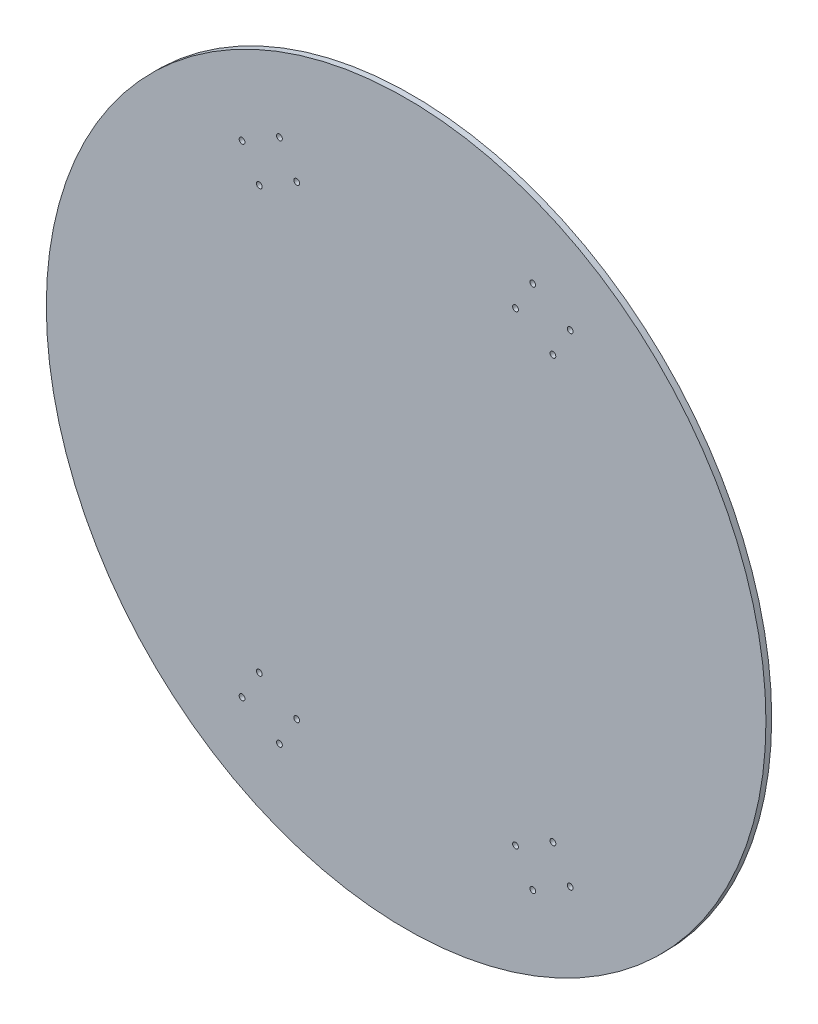
SolidWorks part; units mm, degrees
material "1345 Alloy"
ref_plane "Front Plane" through (0, 0, 0) normal (0, 0, 1) x (1, 0, 0)
ref_plane "Top Plane" through (0, 0, 0) normal (0, 1, 0) x (1, 0, 0)
ref_plane "Right Plane" through (0, 0, 0) normal (1, 0, 0) x (0, 0, -1)
sketch "Sketch1" plane through (0, 0, 0) normal (0, 0, 1) x (1, 0, 0)
  circle A0 centre (0, 0) radius 250
  dimension "D1" = 500
extrude "Boss-Extrude1" add sketch "Sketch1" along normal blind 4
sketch "Sketch2" plane through (0, 0, 4) normal (0, 0, 1) x (1, 0, 0)
  line L0 (0, 0) -> (163.2381, 0) construction
  line L1 (-233.2381, 90) -> (-163.2381, -90) construction
  line L11 (163.2381, -90) -> (163.2381, 90)
  line L12 (-163.2381, 0) -> (0, 0) construction
  line L13 (163.2381, 90) -> (233.2381, -90) construction
  line L14 (163.2381, 90) -> (233.2381, 90)
  line L15 (163.2381, -90) -> (233.2381, -90)
  line L16 (-233.2381, 90) -> (-163.2381, 90)
  line L18 (-233.2381, -90) -> (-163.2381, -90)
  line L19 (-163.2381, 90) -> (-163.2381, -90)
  line L20 (-163.2381, 90) -> (-233.2381, -90) construction
  line L21 (233.2381, 90) -> (163.2381, -90) construction
  circle A0 centre (0, 0) radius 250 construction
  arc A2 (-233.2381, 90) -> (-233.2381, -90) centre (0, 0) ccw
  arc A3 (233.2381, -90) -> (233.2381, 90) centre (0, 0) ccw
  point P18 (0, 0)
  dimension "D1" = 70
  dimension "D3" = 70
extrude "Cut-Extrude1" [suppressed] cut sketch "Sketch2" against normal blind 10
sketch "Sketch5" plane through (0, 0, 4) normal (0, 0, 1) x (1, 0, 0)
  line L8 (-113.9904, 167.4371) -> (-101.9904, 146.6525) construction
  line L10 (88.0096, 182.4371) -> (76.0096, 161.6525) construction
  line L11 (-101.9904, 146.6525) -> (-76.0096, 161.6525) construction
  line L14 (-76.0096, 161.6525) -> (-88.0096, 182.4371) construction
  line L18 (-88.0096, 182.4371) -> (-113.9904, 167.4371) construction
  line L19 (-88.0096, 182.4371) -> (-101.9904, 146.6525) construction
  line L20 (-113.9904, 167.4371) -> (-76.0096, 161.6525) construction
  line L21 (0, 0) -> (-95, 164.5448) construction
  line L22 (76.0096, 161.6525) -> (101.9904, 146.6525) construction
  line L23 (101.9904, 146.6525) -> (113.9904, 167.4371) construction
  line L24 (113.9904, 167.4371) -> (88.0096, 182.4371) construction
  line L29 (113.9904, 167.4371) -> (76.0096, 161.6525) construction
  line L34 (88.0096, 182.4371) -> (101.9904, 146.6525) construction
  line L39 (0, 0) -> (95, 164.5448) construction
  line L59 (113.9904, -167.4371) -> (101.9904, -146.6525) construction
  line L64 (101.9904, -146.6525) -> (76.0096, -161.6525) construction
  line L69 (76.0096, -161.6525) -> (88.0096, -182.4371) construction
  line L74 (88.0096, -182.4371) -> (113.9904, -167.4371) construction
  line L84 (88.0096, -182.4371) -> (101.9904, -146.6525) construction
  line L85 (113.9904, -167.4371) -> (76.0096, -161.6525) construction
  line L86 (0, 0) -> (95, -164.5448) construction
  line L87 (-88.0096, -182.4371) -> (-76.0096, -161.6525) construction
  line L88 (-76.0096, -161.6525) -> (-101.9904, -146.6525) construction
  line L89 (-101.9904, -146.6525) -> (-113.9904, -167.4371) construction
  line L90 (-113.9904, -167.4371) -> (-88.0096, -182.4371) construction
  line L91 (-113.9904, -167.4371) -> (-76.0096, -161.6525) construction
  line L92 (-88.0096, -182.4371) -> (-101.9904, -146.6525) construction
  line L93 (0, 0) -> (-95, -164.5448) construction
  line L101 (-202, -15) -> (-178, -15) construction
  line L102 (-178, -15) -> (-178, 15) construction
  line L103 (-178, 15) -> (-202, 15) construction
  line L104 (-202, 15) -> (-202, -15) construction
  line L105 (-202, 15) -> (-178, -15) construction
  line L106 (-202, -15) -> (-178, 15) construction
  line L107 (0, 0) -> (-190, 0) construction
  line L108 (202, 15) -> (178, 15) construction
  line L109 (178, 15) -> (178, -15) construction
  line L110 (178, -15) -> (202, -15) construction
  line L111 (202, -15) -> (202, 15) construction
  line L112 (202, -15) -> (178, 15) construction
  line L113 (202, 15) -> (178, -15) construction
  line L114 (0, 0) -> (190, 0) construction
  circle A62 centre (-101.9904, 146.6525) radius 2
  circle A63 centre (-76.0096, 161.6525) radius 2
  circle A64 centre (-113.9904, 167.4371) radius 2
  circle A65 centre (-88.0096, 182.4371) radius 2
  circle A70 centre (76.0096, 161.6525) radius 2
  circle A71 centre (101.9904, 146.6525) radius 2
  circle A72 centre (88.0096, 182.4371) radius 2
  circle A73 centre (113.9904, 167.4371) radius 2
  circle A82 centre (101.9904, -146.6525) radius 2
  circle A83 centre (76.0096, -161.6525) radius 2
  circle A84 centre (113.9904, -167.4371) radius 2
  circle A85 centre (88.0096, -182.4371) radius 2
  circle A86 centre (-76.0096, -161.6525) radius 2
  circle A87 centre (-101.9904, -146.6525) radius 2
  circle A88 centre (-88.0096, -182.4371) radius 2
  circle A89 centre (-113.9904, -167.4371) radius 2
  circle A94 centre (-178, -15) radius 2 [skipped]
  circle A95 centre (-178, 15) radius 2 [skipped]
  circle A96 centre (-202, -15) radius 2 [skipped]
  circle A97 centre (-202, 15) radius 2 [skipped]
  circle A98 centre (178, 15) radius 2 [skipped]
  circle A99 centre (178, -15) radius 2 [skipped]
  circle A100 centre (202, 15) radius 2 [skipped]
  circle A101 centre (202, -15) radius 2 [skipped]
  point P5 (0, 0)
  point P6 (0, 0)
  point P15 (0, 0)
  point P17 (0, 0)
  point P18 (0, 0)
  point P27 (0, 0)
  point P29 (0, 0)
  point P30 (0, 0)
  point P33 (-141.1925, 81.5175)
  point P35 (0, 0)
  point P41 (0, 0)
  point P43 (0, 0)
  point P44 (0, 0)
  point P49 (0, 0)
  point P54 (0, 0)
  point P56 (0, 0)
  point P57 (0, 0)
  point P66 (0, 0)
  point P67 (0, 0)
  point P193 (0, 0)
  dimension "D1" = 6
extrude "Cut-Extrude3" cut sketch "Sketch5" against normal blind 10
sketch "Sketch12" plane through (0, 0, 4) normal (0, 0, 1) x (1, 0, 0)
  line L0 (-163.2381, 0) -> (0, 0) construction
  line L1 (207.2381, -25) -> (119.2381, -25)
  line L2 (207.2381, -25) -> (207.2381, 25)
  line L3 (207.2381, 25) -> (119.2381, 25)
  line L4 (-207.2381, 25) -> (-119.2381, 25)
  line L6 (-207.2381, 25) -> (-207.2381, -25)
  line L7 (-207.2381, -25) -> (-119.2381, -25)
  line L8 (-119.2381, 25) -> (-119.2381, -25)
  line L9 (-207.2381, 25) -> (-119.2381, -25) construction
  line L10 (-207.2381, -25) -> (-119.2381, 25) construction
  line L11 (119.2381, -25) -> (119.2381, 25)
  line L12 (163.2381, 0) -> (0, 0) construction
  line L13 (207.2381, -25) -> (119.2381, 25) construction
  line L14 (207.2381, 25) -> (119.2381, -25) construction
  circle A0 centre (-141.2381, 55) radius 6
  circle A1 centre (-141.2381, -55) radius 6
  circle A2 centre (141.2381, -55) radius 6
  circle A3 centre (141.2381, 55) radius 6
  point P23 (0, 0)
  dimension "D8" = 12
  dimension "D9" = 12
  dimension "D1" = 88
  dimension "D2" = 2
  dimension "D4" = 50
extrude "Cut-Extrude7" [suppressed] cut sketch "Sketch12" against normal through all
